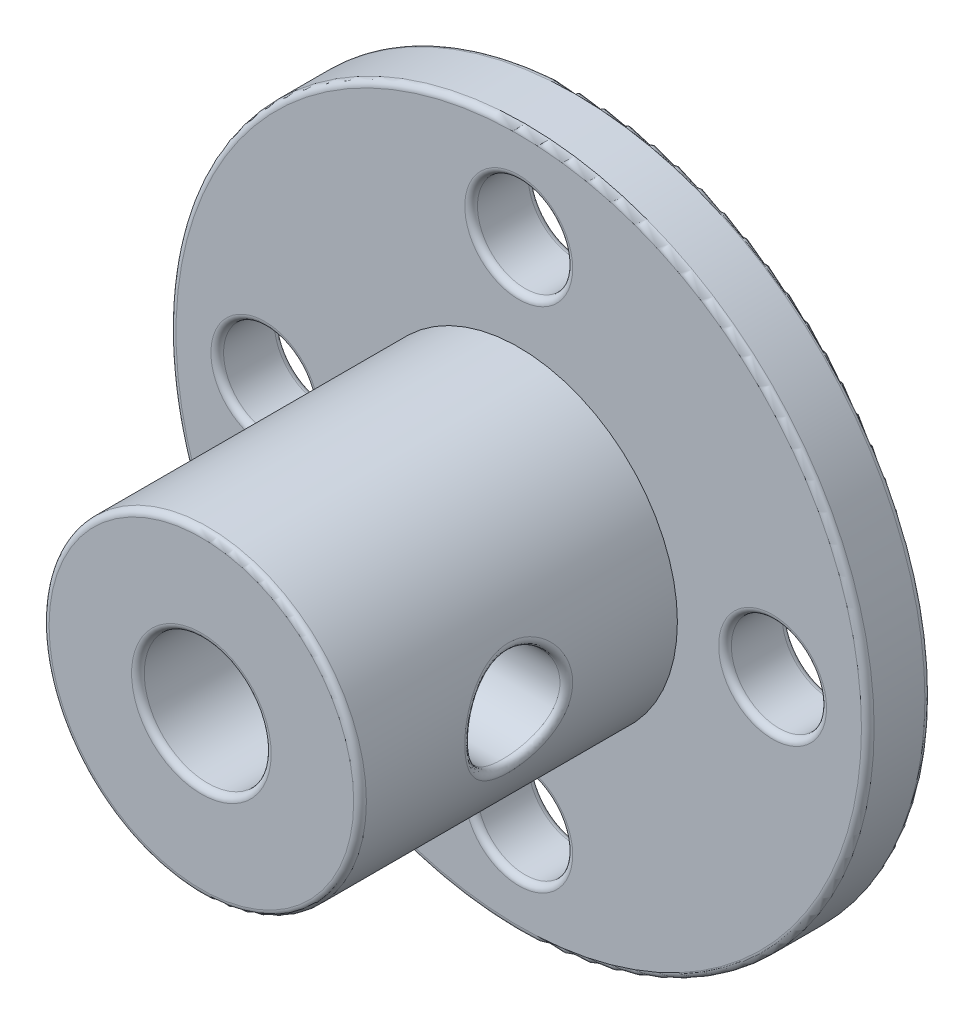
SolidWorks part; units mm, degrees
ref_plane "Front Plane" through (0, 0, 0) normal (0, 0, 1) x (1, 0, 0)
ref_plane "Top Plane" through (0, 0, 0) normal (0, 1, 0) x (1, 0, 0)
ref_plane "Right Plane" through (0, 0, 0) normal (1, 0, 0) x (0, 0, -1)
sketch "Sketch1" plane through (0, 0, 0) normal (0, 0, 1) x (1, 0, 0)
  circle A0 centre (0, 0) radius 11
  dimension "D1" = 22
extrude "Boss-Extrude1" add sketch "Sketch1" along normal blind 2
sketch "Sketch2" plane through (0, 0, 0) normal (0, 0, 1) x (1, 0, 0)
  circle A0 centre (0, 0) radius 5
  dimension "D1" = 10
extrude "Boss-Extrude2" add sketch "Sketch2" along normal blind 10 from surface at 2 starting at face at (11, 0, 2)
sketch "Sketch3" plane through (0, 0, 0) normal (0, 0, 1) x (1, 0, 0)
  circle A0 centre (0, 0) radius 2
  dimension "D1" = 4
extrude "Cut-Extrude1" cut sketch "Sketch3" along normal through all
sketch "Sketch5" plane through (0, 0, 0) normal (0, 0, 1) x (1, 0, 0)
  line L0 (0, -6.6) -> (0, 6.6) construction
  line L1 (6.6, 0) -> (-6.6, 0) construction
  circle A0 centre (0, 8) radius 1.5
  circle A1 centre (8, 0) radius 1.5
  circle A2 centre (0, -8) radius 1.5
  circle A3 centre (-8, 0) radius 1.5
  dimension "D2" = 3
  dimension "D1" = 8
  dimension "D3" = 8
  dimension "D4" = 8
  dimension "D5" = 8
extrude "Cut-Extrude2" cut sketch "Sketch5" along normal through all
sketch "Sketch6" plane through (0, 0, 0) normal (1, 0, 0) x (0, 0, -1)
  line L0 (6.6, 0) -> (-6.6, 0) construction
  line L1 (0, 12.1) -> (0, -12.1) construction
  circle A0 centre (-7, 0) radius 1.5
  dimension "D1" = 3
  dimension "D2" = 7
extrude "Cut-Extrude3" cut sketch "Sketch6" against normal through all both and the other way through all
fillet "Fillet1" radius 0.2 15 edges at (1.5, -8, 0) (-6.5, 0, 0) (2, 0, 0) (1.5, 8, 0) (9.5, 0, 0) (11, 0, 0) (11, 0, 2) (1.5, -8, 2) (-6.5, 0, 2) (1.5, 8, 2) (9.5, 0, 2) (2, 0, 12) (5, 0, 12) (-4.9926, 0.2714, 5.5248) (4.9926, 0.2714, 8.4752)
